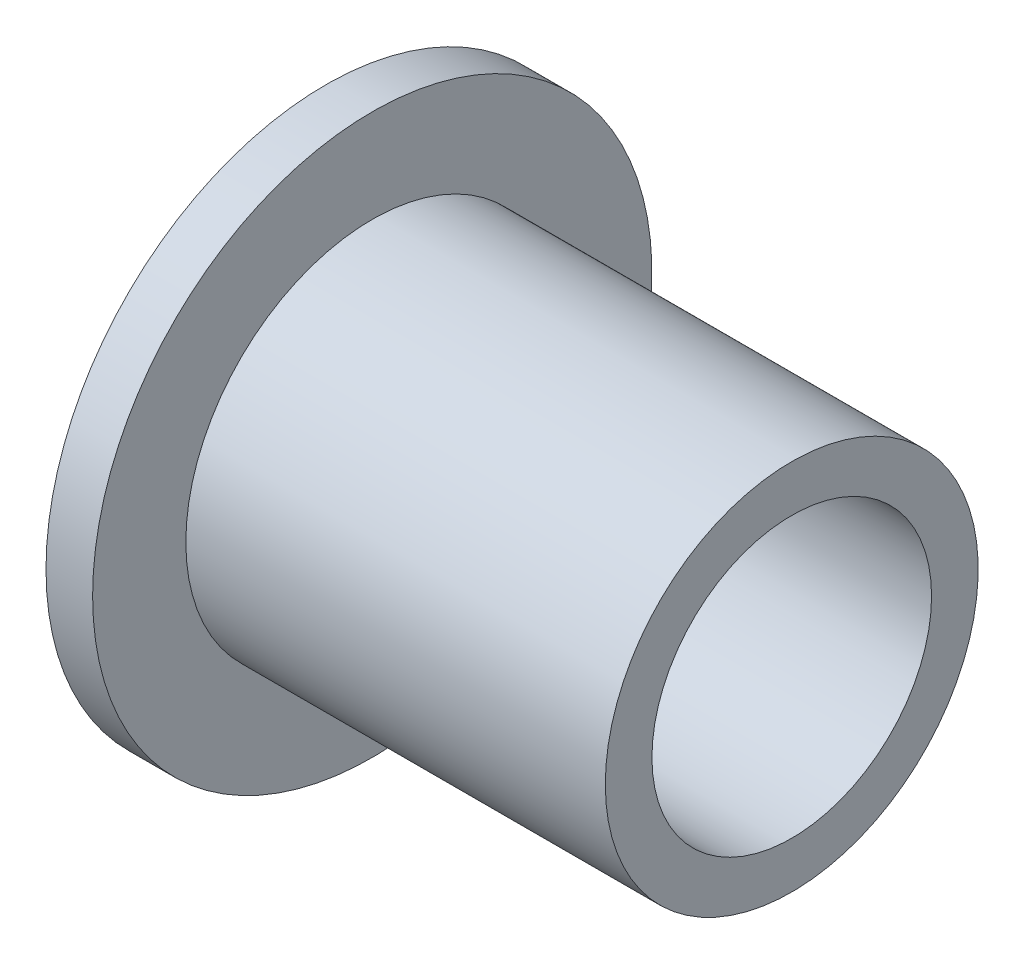
SolidWorks part; units mm, degrees
ref_plane "Plan de face" through (0, 0, 0) normal (0, 0, 1) x (1, 0, 0)
ref_plane "Plan de dessus" through (0, 0, 0) normal (0, 1, 0) x (1, 0, 0)
ref_plane "Plan de droite" through (0, 0, 0) normal (1, 0, 0) x (0, 0, -1)
sketch "Esquisse1" plane through (0, 0, 0) normal (0, 0, 1) x (1, 0, 0)
  line L0 (0, 0) -> (10, 0) construction
  line L2 (10, 3) -> (10, 4)
  line L3 (10, 4) -> (1, 4)
  line L4 (1, 4) -> (1, 6)
  line L5 (1, 6) -> (0, 6)
  line L6 (0, 6) -> (0, 3)
  line L7 (0, 3) -> (10, 3)
  dimension "D1" = 6
  dimension "D2" = 8
  dimension "D3" = 12
  dimension "D4" = 10
  dimension "D5" = 1
revolve "Révolution1" add sketch "Esquisse1" angle 360 about L0
